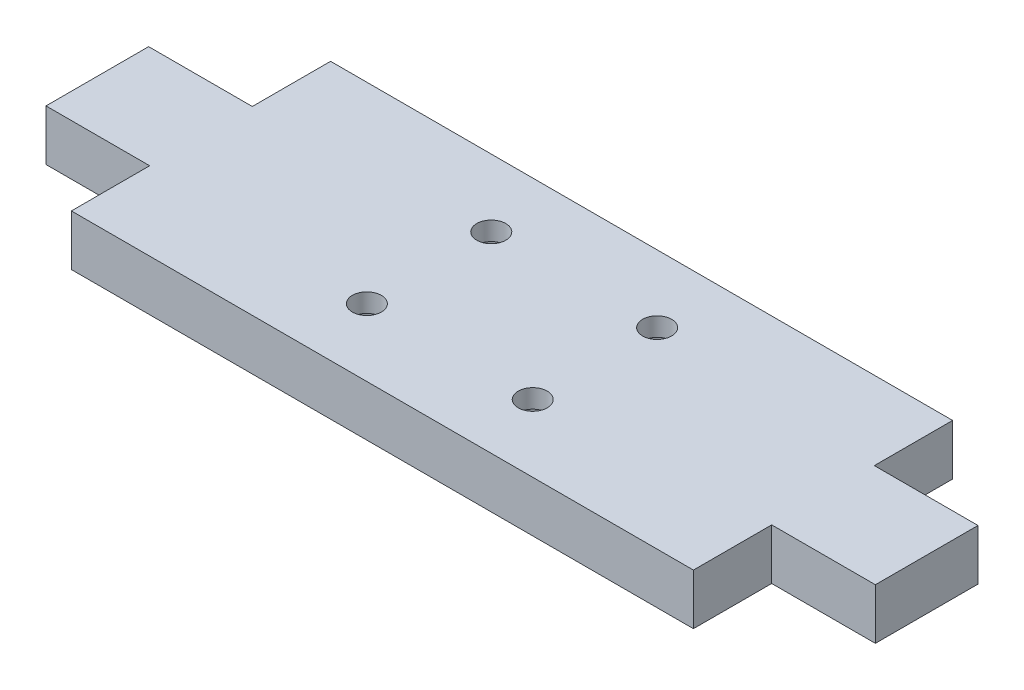
SolidWorks part; units mm, degrees
ref_plane "Front Plane" through (0, 0, 0) normal (0, 0, 1) x (1, 0, 0)
ref_plane "Top Plane" through (0, 0, 0) normal (0, 1, 0) x (1, 0, 0)
ref_plane "Right Plane" through (0, 0, 0) normal (1, 0, 0) x (0, 0, -1)
sketch "Sketch1" plane through (0, 0, 0) normal (1, 0, 0) x (0, 0, -1)
  line L1 (-12.5, -2.45) -> (12.5, -2.45)
  line L2 (-12.5, -2.45) -> (-12.5, 2.45)
  line L3 (-12.5, 2.45) -> (12.5, 2.45)
  line L4 (12.5, -2.45) -> (12.5, 2.45)
  line L5 (-12.5, -2.45) -> (12.5, 2.45) construction
  line L6 (-12.5, 2.45) -> (12.5, -2.45) construction
  point P0 (0, 0)
  dimension "D1" = 4.9
  dimension "D2" = 25
extrude "Boss-Extrude1" add sketch "Sketch1" along normal mid plane 60
sketch "Sketch2" plane through (30, 0, 0) normal (1, 0, 0) x (0, 0, -1)
  line L0 (-12.5, -2.45) -> (12.5, -2.45) construction
  line L1 (-4.95, -2.45) -> (4.95, -2.45)
  line L2 (-4.95, -2.45) -> (-4.95, 2.45)
  line L3 (-4.95, 2.45) -> (4.95, 2.45)
  line L4 (4.95, -2.45) -> (4.95, 2.45)
  line L5 (-4.95, -2.45) -> (4.95, 2.45) construction
  line L6 (-4.95, 2.45) -> (4.95, -2.45) construction
  point P0 (0, 0)
  dimension "D1" = 9.9
  dimension "D2" = 4.9
  dimension "D3" = 4.9
extrude "Boss-Extrude2" add sketch "Sketch2" along normal blind 10
mirror "Mirror1" about plane through (0, 0, 0) normal (1, 0, 0) of "Boss-Extrude2"
sketch "Sketch3" plane through (0, -2.45, 0) normal (0, -1, 0) x (1, 0, 0)
  point P0 (8, 6)
  point P1 (8, -6)
  point P2 (-8, -6)
  point P3 (-8, 6)
  dimension "D1" = 16
  dimension "D2" = 16
  dimension "D3" = 12
  dimension "D4" = 12
  dimension "D5" = 6
  dimension "D6" = 8
hole_wizard "CBORE for M3 SBHCS2" positions "Sketch4" profile "Sketch5" counterbore size "M3" standard "ANSI Metric" end condition through all
sketch "Sketch4" plane through (0, -2.45, 0) normal (0, -1, 0) x (-1, 0, 0)
  point P0 (-8, 6)
  point P3 (8, 6)
  point P6 (8, -6)
  point P9 (-8, -6)
sketch "Sketch5" plane through (8, -2.45, -6) normal (1, 0, 0) x (0, 0, -1)
  line L0 (0, 0) -> (0, 4.9)
  line L1 (0, 4.9) -> (1.4, 4.9)
  line L3 (1.4, 4.9) -> (1.4, 3.1)
  line L4 (1.4, 3.1) -> (2.75, 3.1)
  line L5 (2.75, 3.1) -> (2.75, 0)
  line L7 (2.75, 0) -> (0, 0)
  line L11 (0, -6.35) -> (0, 107.95) construction
  dimension "Thru Hole Dia." = 2.8
  dimension "Thru Hole Depth" = 4.9
  dimension "C'Bore Dia." = 5.5
  dimension "C'Bore Depth" = 3.1
